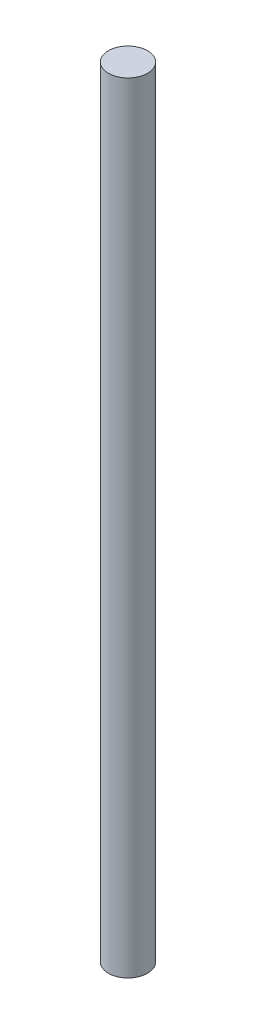
SolidWorks part; units mm, degrees
ref_plane "Ebene vorne" through (0, 0, 0) normal (0, 0, 1) x (1, 0, 0)
ref_plane "Ebene oben" through (0, 0, 0) normal (0, 1, 0) x (1, 0, 0)
ref_plane "Ebene rechts" through (0, 0, 0) normal (1, 0, 0) x (0, 0, -1)
sketch "Skizze1" plane through (0, 0, 0) normal (0, 1, 0) x (1, 0, 0)
  circle A0 centre (0, 0) radius 1.5
  dimension "D1" = 3
extrude "Aufsatz-Linear austragen1" add sketch "Skizze1" along normal blind 59.7
